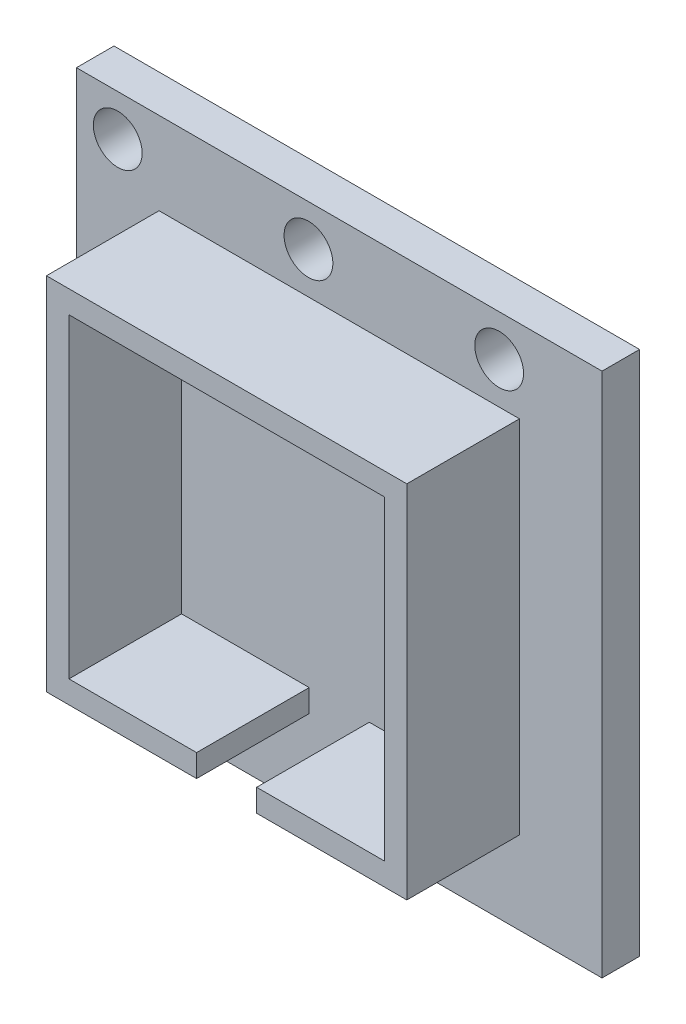
SolidWorks part; units mm, degrees
ref_plane "Front Plane" through (0, 0, 0) normal (0, 0, 1) x (1, 0, 0)
ref_plane "Top Plane" through (0, 0, 0) normal (0, 1, 0) x (1, 0, 0)
ref_plane "Right Plane" through (0, 0, 0) normal (1, 0, 0) x (0, 0, -1)
sketch "Sketch1" plane through (0, 0, 0) normal (0, 0, 1) x (1, 0, 0)
  line L1 (0, 0) -> (70, 0)
  line L2 (0, 0) -> (0, 70)
  line L3 (0, 70) -> (70, 70)
  line L4 (70, 0) -> (70, 70)
  dimension "D1" = 70
  dimension "D2" = 70
extrude "Extrude1" add sketch "Sketch1" along normal blind 5
sketch "Sketch2" plane through (0, 0, 5) normal (0, 0, 1) x (1, 0, 0)
  line L1 (11, 11) -> (59, 11)
  line L2 (11, 11) -> (11, 59)
  line L3 (11, 59) -> (59, 59)
  line L4 (59, 11) -> (59, 59)
  line L5 (70, 70) -> (0, 70) construction
  line L6 (70, 0) -> (70, 70) construction
  line L7 (0, 0) -> (70, 0) construction
  line L8 (0, 70) -> (0, 0) construction
  line L10 (14, 56) -> (56, 56)
  line L11 (14, 56) -> (14, 14)
  line L12 (14, 14) -> (56, 14)
  line L13 (56, 56) -> (56, 14)
  dimension "D1" = 11
  dimension "D2" = 11
  dimension "D3" = 11
  dimension "D4" = 11
  dimension "D5" = 42
  dimension "D6" = 42
  dimension "D7" = 3
  dimension "D8" = 3
extrude "Extrude2" add sketch "Sketch2" along normal blind 15
sketch "Sketch5" plane through (0, 0, 5) normal (0, 0, 1) x (1, 0, 0)
  line L0 (0, 70) -> (0, 0) construction
  line L1 (70, 70) -> (0, 70) construction
  line L2 (70, 0) -> (70, 70) construction
  line L4 (11, 0) -> (-11, 0) construction
  circle A0 centre (5.5, 64.5) radius 3.25
  circle A1 centre (30.9, 64.5) radius 3.25
  circle A2 centre (56.3, 64.5) radius 3.25
  circle A3 centre (5.5, 39.1) radius 3.25
  circle A4 centre (5.5, 13.7) radius 3.25
  dimension "D1" = 6.5
  dimension "D2" = 5.5
  dimension "D3" = 5.5
  dimension "D4" = 25.4
  dimension "D5" = 5.5
  dimension "D6" = 5.5
  dimension "D7" = 25.4
  dimension "D8" = 5.5
  dimension "D9" = 25.4
  dimension "D10" = 13.7
  dimension "D11" = 5.5
  dimension "D12" = 13.7
extrude "Cut-Extrude2" cut sketch "Sketch5" against normal through all
sketch "Sketch6" plane through (0, 0, 20) normal (0, 0, 1) x (1, 0, 0)
  line L0 (11, 0) -> (-11, 0) construction
  line L1 (31, 18) -> (39, 18)
  line L2 (31, 18) -> (31, 10)
  line L3 (31, 10) -> (39, 10)
  line L4 (39, 18) -> (39, 10)
  line L5 (56, 14) -> (56, 56) construction
  line L6 (14, 56) -> (14, 14) construction
  dimension "D1" = 8
  dimension "D2" = 10
  dimension "D3" = 17
  dimension "D4" = 17
extrude "Cut-Extrude3" cut sketch "Sketch6" against normal blind 15
